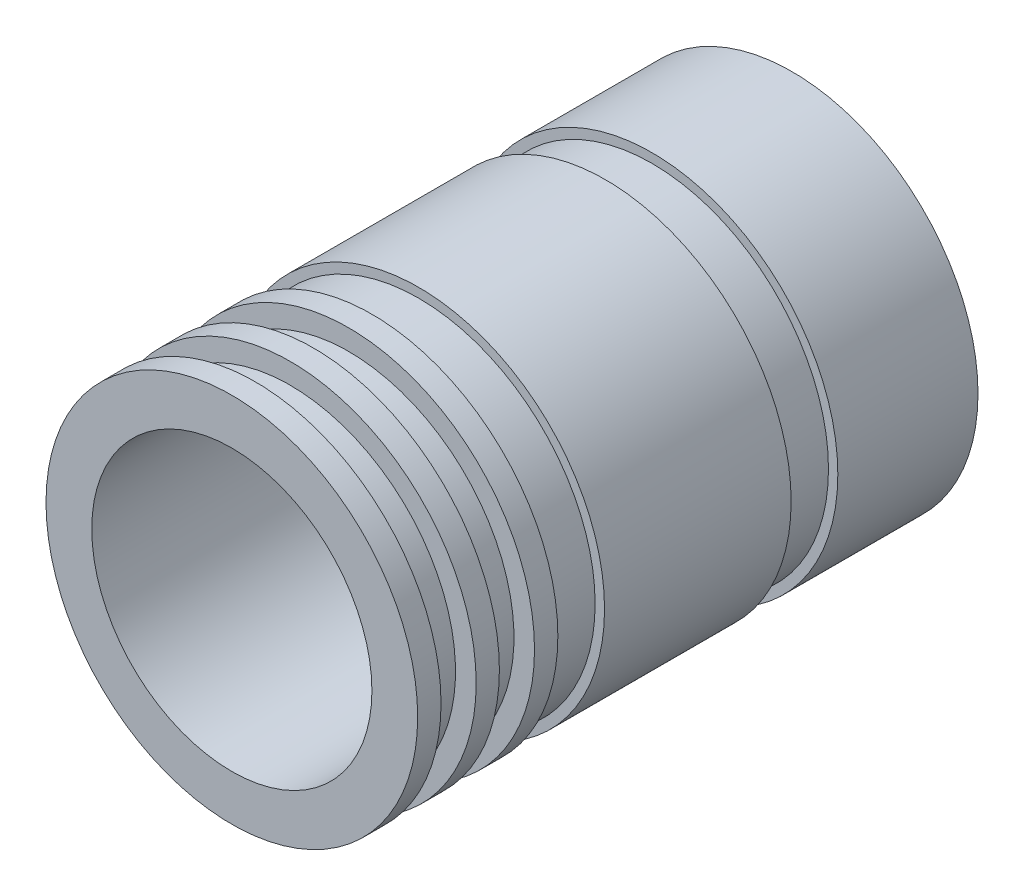
SolidWorks part; units mm, degrees
ref_plane "Front Plane" through (0, 0, 0) normal (0, 0, 1) x (1, 0, 0)
ref_plane "Top Plane" through (0, 0, 0) normal (0, 1, 0) x (1, 0, 0)
ref_plane "Right Plane" through (0, 0, 0) normal (1, 0, 0) x (0, 0, -1)
sketch "Sketch1" plane through (0, 0, 0) normal (0, 0, 1) x (1, 0, 0)
  circle A0 centre (0, 0) radius 25.273
  dimension "D1" = 50.546
extrude "Boss-Extrude1" add sketch "Sketch1" along normal blind 76.2
sketch "Sketch5" plane through (0, 0, 76.2) normal (0, 0, 1) x (1, 0, 0)
  circle A0 centre (0, 0) radius 19.05
  dimension "D1" = 38.1
extrude "Cut-Extrude2" cut sketch "Sketch5" against normal blind 76.2
ref_plane "Plane1" through (0, 0, 76.2) normal (-1, 0, 0) x (0, 1, 0)
ref_plane "Plane2" through (0, 0, 76.2) normal (-1, 0, 0) x (0, 1, 0)
ref_plane "Plane3" through (0, 0, 76.2) normal (-1, 0, 0) x (0, 1, 0)
ref_plane "Plane4" through (0, 0, 76.2) normal (-1, 0, 0) x (0, 1, 0)
sketch "Groove" plane through (0, 0, 0) normal (1, 0, 0) x (0, 0, -1)
  line L0 (0, 25.273) -> (-76.2, 25.273) construction
  line L1 (-76.2, 25.273) -> (-76.2, -25.273) construction
  line L2 (-73.025, 25.273) -> (-73.025, 22.479)
  line L3 (-73.025, 22.479) -> (-68.2625, 22.479)
  line L4 (-68.2625, 22.479) -> (-68.2447, 25.273)
  line L5 (-68.2447, 25.273) -> (-65.0875, 25.273)
  line L6 (-65.0875, 25.273) -> (-65.0875, 22.479)
  line L7 (-65.0875, 22.479) -> (-60.3123, 22.479)
  line L8 (-60.3123, 22.479) -> (-60.3123, 25.273)
  line L9 (-60.3123, 25.273) -> (-57.1373, 25.273)
  line L10 (-57.1373, 25.273) -> (-57.1373, 24.003)
  line L11 (-57.1373, 24.003) -> (-50.8, 24.003)
  line L12 (-50.8, 24.003) -> (-50.7873, 25.273)
  line L13 (-50.7873, 25.273) -> (-50.7873, 27.7239)
  line L14 (-50.7873, 27.7239) -> (-73.025, 27.7239)
  line L15 (-73.025, 27.7239) -> (-73.025, 25.273)
  line L16 (-38.1, 25.273) -> (-38.1, -25.3913) construction
  line L17 (-19.0627, 27.7239) -> (-25.4127, 27.7239)
  line L19 (-25.4127, 25.273) -> (-25.4127, 27.7239)
  line L20 (-25.4, 24.003) -> (-25.4127, 25.273)
  line L21 (-19.0627, 24.003) -> (-25.4, 24.003)
  line L22 (-19.0627, 25.273) -> (-19.0627, 24.003)
  line L31 (-19.0627, 25.273) -> (-19.0627, 27.7239)
  point P0 (-73.025, 25.273)
  point P1 (-68.2625, 25.273)
  point P4 (-68.2447, 25.273)
  point P5 (-65.0875, 25.273)
  point P7 (-60.3123, 25.273)
  point P9 (-57.1373, 25.273)
  point P10 (-50.7873, 25.273)
  point P11 (-50.8, 25.273)
  point P14 (-38.1, 25.273)
  point P27 (-38.1, -25.3913)
  point P44 (-25.4, 25.273)
  dimension "D1" = 3.175
  dimension "D2" = 4.7625
  dimension "D3" = 3.175
  dimension "D4" = 4.7752
  dimension "D5" = 3.175
  dimension "D6" = 2.794
  dimension "D7" = 25.4
  dimension "D8" = 2.794
  dimension "D9" = 1.27
ref_plane "Plane9" through (0, 0, 60.3123) normal (0, 0, 1) x (1, 0, 0)
sketch "groove path" plane through (0, 0, 60.3123) normal (0, 0, 1) x (1, 0, 0)
  circle A0 centre (0, 0) radius 25.273 construction
  circle A1 centre (0, 0) radius 25.273
sweep "Cut-Sweep4" cut profiles "Groove" path "groove path"
sketch "Sketch6" plane through (0, 0, 0) normal (1, 0, 0) x (0, 0, -1)
  line L1 (-3.1281, 0) -> (-15.8281, 0)
  line L3 (0, 25.273) -> (-19.0627, 25.273) construction
  line L10 (-3.1281, 21.844) -> (-7.9375, 21.844)
  line L11 (-7.9375, 21.844) -> (-7.9375, 18.034)
  line L12 (-7.9375, 18.034) -> (-11.1125, 18.034)
  line L13 (-11.1125, 18.034) -> (-11.1125, 21.8443)
  line L14 (-11.1125, 21.8443) -> (-15.8281, 21.8443)
  line L15 (-15.8281, 21.8443) -> (-15.8281, 0)
  line L17 (-3.1281, 0) -> (-3.1281, 21.844)
  point P4 (-7.8906, 25.273)
  point P5 (-3.1281, 25.273)
  point P6 (-11.0656, 25.273)
  point P9 (-15.8281, 25.273)
  dimension "D2" = 4.7625
  dimension "D3" = 3.175
  dimension "D4" = 4.7625
  dimension "D6" = 3.429
  dimension "D8" = 3.81
ref_plane "Plane14" through (0, 0, 11.0656) normal (0, 0, -1) x (-1, 0, 0)
sketch "Sketch14" plane through (0, 0, 11.0656) normal (0, 0, -1) x (-1, 0, 0)
  circle A0 centre (0, 0) radius 19.05 construction
  circle A1 centre (0, 0) radius 19.05
sweep "Cut-Sweep5" cut profiles "Sketch6" path "Sketch14"
